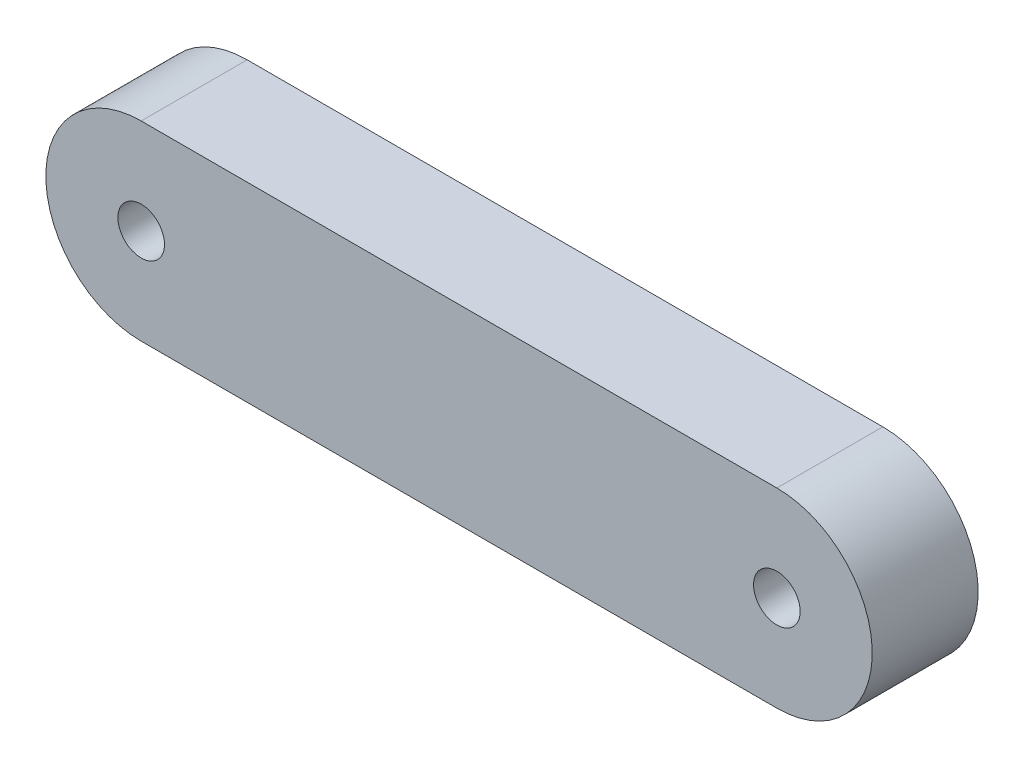
SolidWorks part; units mm, degrees
ref_plane "Front Plane" through (0, 0, 0) normal (0, 0, 1) x (1, 0, 0)
ref_plane "Top Plane" through (0, 0, 0) normal (0, 1, 0) x (1, 0, 0)
ref_plane "Right Plane" through (0, 0, 0) normal (1, 0, 0) x (0, 0, -1)
sketch "Sketch1" plane through (0, 0, 0) normal (0, 0, 1) x (1, 0, 0)
  line L1 (-15, -4.5) -> (15, -4.5)
  line L3 (-15, 4.5) -> (15, 4.5)
  line L5 (-15, -4.5) -> (15, 4.5) construction
  line L6 (-15, 4.5) -> (15, -4.5) construction
  arc A0 (-15, 4.5) -> (-15, -4.5) centre (-15, 0) ccw
  arc A1 (15, -4.5) -> (15, 4.5) centre (15, 0) ccw
  point P0 (0, 0)
  dimension "D1" = 30
  dimension "D2" = 9
extrude "Boss-Extrude1" add sketch "Sketch1" along normal blind 5
sketch "Sketch2" plane through (0, 0, 5) normal (0, 0, 1) x (1, 0, 0)
  circle A0 centre (-15, 0) radius 1.1
  circle A1 centre (15, 0) radius 1.1
  dimension "D1" = 2.2
extrude "Cut-Extrude1" cut sketch "Sketch2" against normal through all
sketch "Sketch3" plane through (0, 0, 0) normal (0, 0, -1) x (-1, 0, 0)
  line L0 (-11.8188, 4.5) -> (-11.8188, -4.5)
  line L1 (-15, 4.5) -> (15, 4.5) construction
  line L2 (15, -4.5) -> (-15, -4.5) construction
